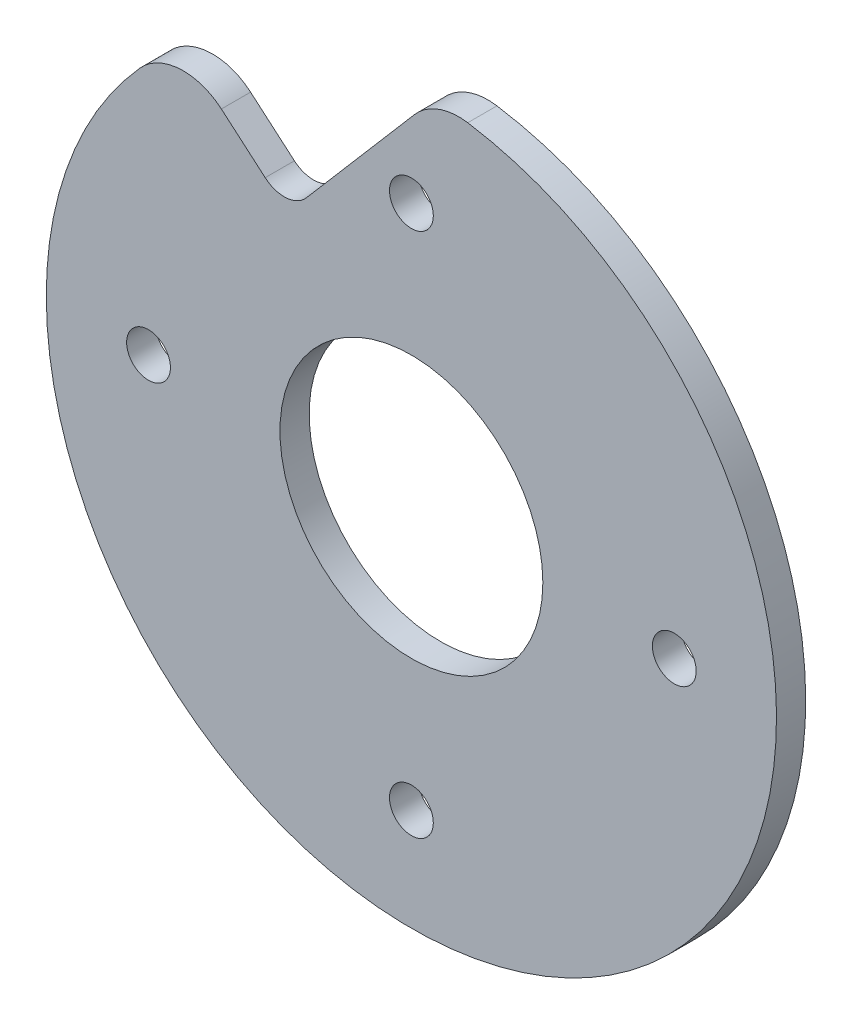
SolidWorks part; units mm, degrees
ref_plane "前视基准面" through (0, 0, 0) normal (0, 0, 1) x (1, 0, 0)
ref_plane "上视基准面" through (0, 0, 0) normal (0, 1, 0) x (1, 0, 0)
ref_plane "右视基准面" through (0, 0, 0) normal (1, 0, 0) x (0, 0, -1)
sketch "Model" plane through (0, 0, 0) normal (0, 0, 1) x (1, 0, 0)
  line L0 (0.2032, 23.3516) -> (-7.1912, 14.7247)
  line L1 (-10.0113, 14.5077) -> (-13.0115, 17.0793)
  circle A0 centre (-18, 0) radius 1.5
  circle A1 centre (18, 0) radius 1.5
  circle A2 centre (0, 0) radius 9
  arc A3 (-18.5888, 16.7169) -> (3.8575, 24.7006) centre (0, 0) ccw
  circle A4 centre (0, 18) radius 1.5
  circle A5 centre (0, -18) radius 1.5
  arc A6 (-13.0115, 17.0793) -> (-18.5888, 16.7169) centre (-15.6146, 14.0422) ccw
  arc A7 (3.8575, 24.7006) -> (0.2032, 23.3516) centre (3.2403, 20.7485) ccw
  arc A8 (-10.0113, 14.5077) -> (-7.1912, 14.7247) centre (-8.7097, 16.0262) ccw
  dimension "D1" = 3
extrude "凸台-拉伸1" add sketch "Model" along normal blind 2
